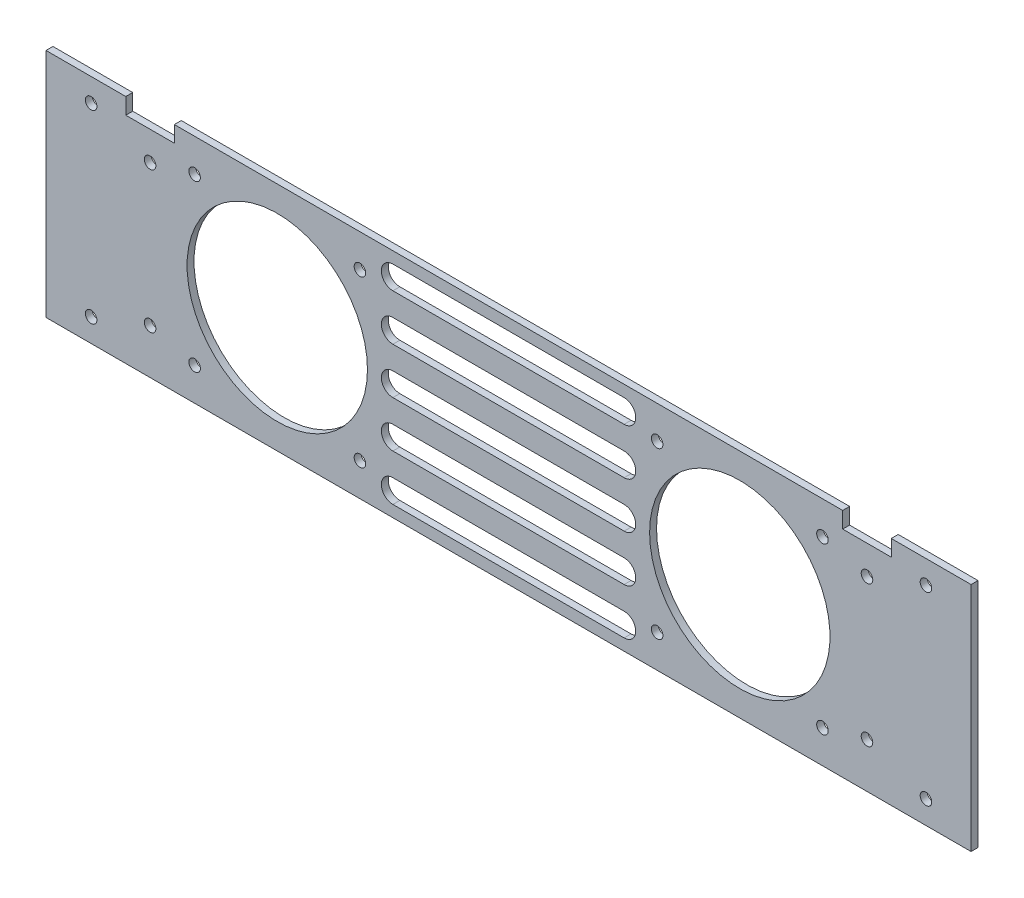
SolidWorks part; units mm, degrees
ref_plane "Front Plane" through (0, 0, 0) normal (0, 0, 1) x (1, 0, 0)
ref_plane "Top Plane" through (0, 0, 0) normal (0, 1, 0) x (1, 0, 0)
ref_plane "Right Plane" through (0, 0, 0) normal (1, 0, 0) x (0, 0, -1)
sketch "Sketch1" plane through (0, 0, 0) normal (0, 0, 1) x (1, 0, 0)
  line L1 (-200, -50) -> (200, -50)
  line L2 (-200, -50) -> (-200, 50)
  line L3 (-200, 50) -> (200, 50)
  line L4 (200, -50) -> (200, 50)
  point P4 (0, 50)
  point P7 (-200, 0)
  dimension "D1" = 100
  dimension "D2" = 400
extrude "Boss-Extrude1" add sketch "Sketch1" along normal blind 3
sketch "Sketch2" plane through (0, 0, 3) normal (0, 0, 1) x (1, 0, 0)
  line L0 (0, -1000) -> (0, 49000) construction
  line L1 (-200, 50) -> (-200, -50) construction
  line L6 (135.75, 35.75) -> (135.75, -35.75) construction
  line L7 (64.25, -35.75) -> (135.75, -35.75) construction
  line L8 (64.25, 35.75) -> (64.25, -35.75) construction
  line L9 (-64.25, 35.75) -> (-135.75, 35.75) construction
  line L10 (-64.25, 35.75) -> (-64.25, -35.75) construction
  line L11 (-64.25, -35.75) -> (-135.75, -35.75) construction
  line L12 (-135.75, 35.75) -> (-135.75, -35.75) construction
  line L13 (64.25, 35.75) -> (135.75, 35.75) construction
  circle A0 centre (-64.25, 35.75) radius 2.5
  circle A1 centre (-64.25, -35.75) radius 2.5
  circle A2 centre (-135.75, -35.75) radius 2.5
  circle A3 centre (-135.75, 35.75) radius 2.5
  circle A4 centre (-100, 0) radius 39
  circle A5 centre (100, 0) radius 39
  circle A6 centre (135.75, 35.75) radius 2.5
  circle A7 centre (135.75, -35.75) radius 2.5
  circle A8 centre (64.25, -35.75) radius 2.5
  circle A9 centre (64.25, 35.75) radius 2.5
  point P1 (-100, 0)
  point P8 (-100, 35.75)
  point P11 (-200, 0)
  point P16 (-135.75, 0)
  dimension "D2" = 5
  dimension "D4" = 78
  dimension "D1" = 100
  dimension "D3" = 71.5
extrude "Cut-Extrude1" cut sketch "Sketch2" against normal through all
sketch "Sketch3" plane through (0, 0, 3) normal (0, 0, 1) x (1, 0, 0)
  line L0 (-1000, 0) -> (49000, 0) construction
  line L1 (0, -1000) -> (0, 49000) construction
  line L2 (-50, 0) -> (50, 0) construction
  line L3 (-50, 5) -> (50, 5)
  line L4 (-50, -5) -> (50, -5)
  line L5 (-50, 20) -> (50, 20) construction
  line L6 (-50, 25) -> (50, 25)
  line L7 (-50, 15) -> (50, 15)
  line L8 (-50, 40) -> (50, 40) construction
  line L9 (-50, 45) -> (50, 45)
  line L10 (-50, 35) -> (50, 35)
  line L11 (-50, 0) -> (-50, 20) construction
  line L12 (-50, -40) -> (50, -40) construction
  line L13 (-50, -45) -> (50, -45)
  line L14 (-50, -35) -> (50, -35)
  line L15 (-50, -20) -> (50, -20) construction
  line L16 (-50, -25) -> (50, -25)
  line L17 (-50, -15) -> (50, -15)
  arc A0 (-50, 5) -> (-50, -5) centre (-50, 0) ccw
  arc A1 (50, -5) -> (50, 5) centre (50, 0) ccw
  arc A2 (-50, 25) -> (-50, 15) centre (-50, 20) ccw
  arc A3 (50, 15) -> (50, 25) centre (50, 20) ccw
  arc A4 (-50, 45) -> (-50, 35) centre (-50, 40) ccw
  arc A5 (50, 35) -> (50, 45) centre (50, 40) ccw
  arc A6 (-50, -45) -> (-50, -35) centre (-50, -40) cw
  arc A7 (50, -35) -> (50, -45) centre (50, -40) cw
  arc A8 (-50, -25) -> (-50, -15) centre (-50, -20) cw
  arc A9 (50, -15) -> (50, -25) centre (50, -20) cw
  point P7 (0, 0)
  point P15 (0, 20)
  point P22 (0, 40)
  point P30 (0, -40)
  point P37 (0, -20)
  dimension "D3" = 5
  dimension "D1" = 100
  dimension "D2" = 3
  dimension "D4" = 20
extrude "Cut-Extrude2" cut sketch "Sketch3" against normal through all
sketch "Sketch4" plane through (0, 0, 3) normal (0, 0, 1) x (1, 0, 0)
  line L0 (-1000, 0) -> (49000, 0) construction
  line L1 (-200, -50) -> (200, -50) construction
  line L2 (-200, 50) -> (-200, -50) construction
  line L3 (0, -1000) -> (0, 49000) construction
  circle A0 centre (-155, -30.5) radius 2.5
  circle A1 centre (-155, 30.5) radius 2.5
  circle A2 centre (155, 30.5) radius 2.5
  circle A3 centre (155, -30.5) radius 2.5
  dimension "D2" = 5
  dimension "D1" = 19.5
  dimension "D3" = 45
extrude "Cut-Extrude3" cut sketch "Sketch4" against normal up to next
sketch "Sketch5" plane through (0, 0, 3) normal (0, 0, 1) x (1, 0, 0)
  line L0 (200, 50) -> (-200, 50) construction
  line L1 (-200, -50) -> (200, -50) construction
  line L2 (-200, 50) -> (-200, -50) construction
  line L3 (0, -1000) -> (0, 49000) construction
  circle A0 centre (-180.5, -40) radius 2.5
  circle A1 centre (-180.5, 40) radius 2.5
  circle A3 centre (180.5, 40) radius 2.5
  circle A4 centre (180.5, -40) radius 2.5
  dimension "D2" = 5
  dimension "D4" = 19.5
  dimension "D1" = 10
  dimension "D3" = 10
extrude "Cut-Extrude4" cut sketch "Sketch5" against normal through all
sketch "Sketch6" plane through (0, 0, 3) normal (0, 0, 1) x (1, 0, 0)
  line L0 (0, -1000) -> (0, 49000) construction
  line L1 (-155, -969.5) -> (-155, 49030.5) construction
  line L2 (200, 50) -> (-200, 50) construction
  line L3 (-165.5, 43) -> (-144.5, 43)
  line L4 (-165.5, 43) -> (-165.5, 50)
  line L5 (-165.5, 50) -> (-144.5, 50)
  line L6 (-144.5, 43) -> (-144.5, 50)
  line L7 (-165.5, 43) -> (-144.5, 50) construction
  line L8 (-165.5, 50) -> (-144.5, 43) construction
  line L9 (165.5, 50) -> (144.5, 43) construction
  line L10 (165.5, 43) -> (144.5, 50) construction
  line L11 (144.5, 43) -> (144.5, 50)
  line L12 (165.5, 50) -> (144.5, 50)
  line L13 (165.5, 43) -> (165.5, 50)
  line L14 (165.5, 43) -> (144.5, 43)
  point P4 (-155, 46.5)
  point P17 (155, 46.5)
  dimension "D1" = 7
  dimension "D2" = 21
extrude "Cut-Extrude5" cut sketch "Sketch6" against normal up to next
